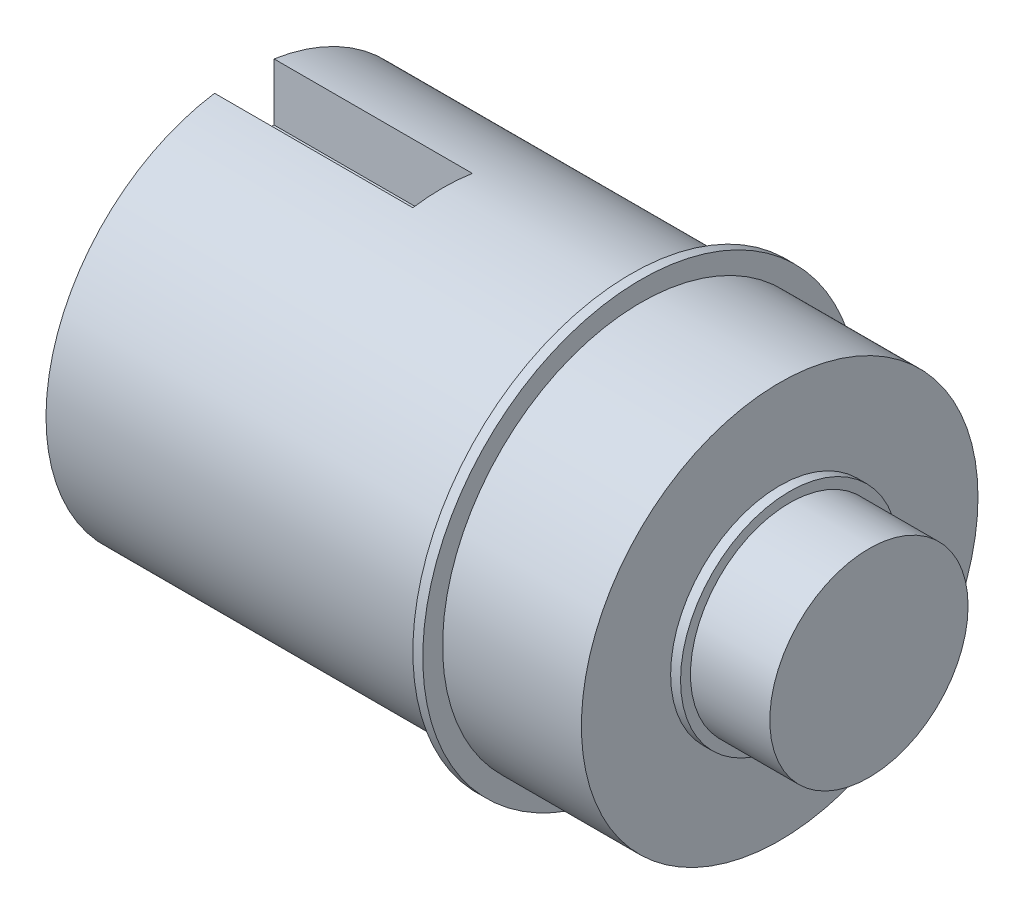
SolidWorks part; units mm, degrees
ref_plane "Ebene vorne" through (0, 0, 0) normal (0, 0, 1) x (1, 0, 0)
ref_plane "Ebene oben" through (0, 0, 0) normal (0, 1, 0) x (1, 0, 0)
ref_plane "Ebene rechts" through (0, 0, 0) normal (1, 0, 0) x (0, 0, -1)
sketch "Sketch1" plane through (0, 0, 0) normal (0, 0, 1) x (1, 0, 0)
  line L0 (0, 0) -> (-20.7193, 0) construction
  line L1 (0, 0) -> (0, 10)
  line L2 (0, 10) -> (27, 10)
  line L3 (27, 10) -> (27, 5.5)
  line L4 (27, 5.5) -> (27.5, 5.5)
  line L5 (27.5, 5.5) -> (27.5, 5)
  line L6 (27.5, 5) -> (31.5, 5)
  line L7 (31.5, 5) -> (31.5, 0)
  line L8 (31.5, 0) -> (0, 0)
  line L9 (19.5, 10) -> (19.5, 11)
  line L10 (19.5, 11) -> (20, 11)
  line L11 (20, 11) -> (20, 10)
  dimension "D1" = 27
  dimension "D2" = 20
  dimension "D3" = 11
  dimension "D4" = 10
  dimension "D5" = 4
  dimension "D6" = 0.5
  dimension "D7" = 1
  dimension "D8" = 0.5
  dimension "D9" = 19.5
revolve "Revolve1" add sketch "Sketch1" angle 360 about L0
sketch "Sketch2" plane through (0, 0, 0) normal (-1, 0, 0) x (0, 0, 1)
  line L5 (-1.5, 7) -> (1.5, 7)
  line L6 (-1.5, 7) -> (-1.5, 13)
  line L7 (-1.5, 13) -> (1.5, 13)
  line L8 (1.5, 7) -> (1.5, 13)
  line L9 (-1.5, 7) -> (1.5, 13) construction
  line L10 (-1.5, 13) -> (1.5, 7) construction
  circle A1 centre (0, 0) radius 10 construction
  point P0 (0, 10)
  dimension "D1" = 3
  dimension "D2" = 3
extrude "Cut-Extrude1" cut sketch "Sketch2" against normal blind 10
